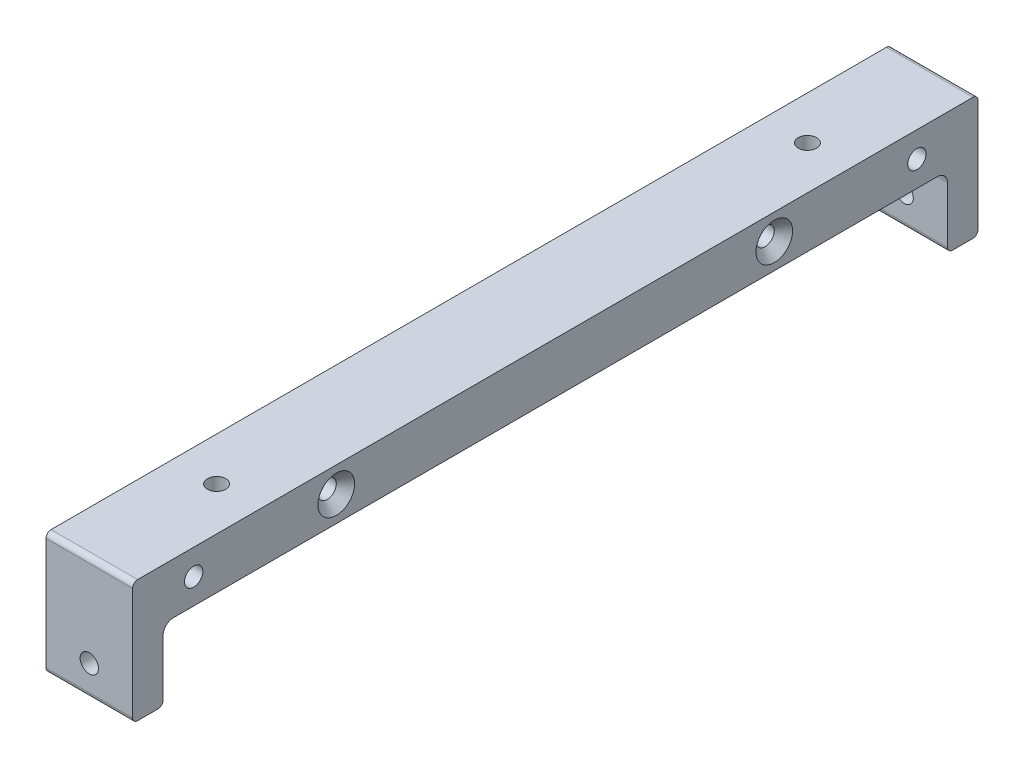
SolidWorks part; units mm, degrees
material "6061 Alloy"
ref_plane "Frontal" through (0, 0, 0) normal (0, 0, 1) x (1, 0, 0)
ref_plane "Superior" through (0, 0, 0) normal (0, 1, 0) x (1, 0, 0)
ref_plane "Direito" through (0, 0, 0) normal (1, 0, 0) x (0, 0, -1)
sketch "Sketch1" plane through (0, 0, 0) normal (0, 0, 1) x (1, 0, 0)
  line L1 (-4.25, -6) -> (4.25, -6)
  line L2 (-4.25, -6) -> (-4.25, 6)
  line L3 (-4.25, 6) -> (4.25, 6)
  line L4 (4.25, -6) -> (4.25, 6)
  line L5 (-4.25, -6) -> (4.25, 6) construction
  line L6 (-4.25, 6) -> (4.25, -6) construction
  point P0 (0, 0)
  dimension "D1" = 8.5
  dimension "D2" = 12
extrude "Boss-Extrude1" add sketch "Sketch1" along normal mid plane 83
sketch "Sketch2" plane through (4.25, 0, 0) normal (1, 0, 0) x (0, 0, -1)
  line L0 (-37.5, 1) -> (37.5, 1)
  line L1 (38.5, 0) -> (38.5, -6)
  line L2 (-41.5, -6) -> (41.5, -6) construction
  line L3 (38.5, -6) -> (-38.5, -6)
  line L4 (-38.5, -6) -> (-38.5, 0)
  line L5 (-41.5, 6) -> (41.5, 6) construction
  line L6 (-41.5, -6) -> (-41.5, 6) construction
  line L7 (41.5, -6) -> (41.5, 6) construction
  arc A0 (-37.5, 1) -> (-38.5, 0) centre (-37.5, 0) ccw
  arc A1 (37.5, 1) -> (38.5, 0) centre (37.5, 0) cw
  dimension "D4" = 1
  dimension "D5" = 1
  dimension "D1" = 5
  dimension "D2" = 3
  dimension "D3" = 3
extrude "Cut-Extrude1" cut sketch "Sketch2" against normal through all
hole_wizard "M1.6 Hole1-FixingPCB" positions "Sketch4" profile "Sketch3" countersink size "M1.6" standard "DIN" end condition through all
sketch "Sketch4" plane through (4.25, 0, 0) normal (1, 0, 0) x (0, 0, -1)
  line L0 (-41.5, 6) -> (41.5, 6) construction
  line L1 (-41.5, -6) -> (-41.5, 6) construction
  line L2 (41.5, -6) -> (41.5, 6) construction
  point P0 (-21.5, 3.5)
  point P2 (21.5, 3.5)
  dimension "D1" = 2.5
  dimension "D2" = 20
  dimension "D3" = 20
sketch "Sketch3" plane through (4.25, 3.5, 21.5) normal (0, 1, 0) x (0, 0, -1)
  line L0 (0, 0) -> (0, 8.5)
  line L1 (0, 8.5) -> (0.9, 8.5)
  line L2 (0.9, 8.5) -> (0.9, 0.9)
  line L3 (0.9, 0.9) -> (1.8, 0)
  line L5 (1.8, 0) -> (0, 0)
  line L6 (-0.9, 0.9) -> (-1.8, 0) construction
  line L11 (0, -6.35) -> (0, 107.95) construction
  dimension "Thru Hole Dia." = 1.8
  dimension "Thru Hole Depth" = 8.5
  dimension "Near C'Sink Dia." = 3.6
  dimension "Near C'Sink Angle" = 90
fillet "Fillet1" radius 0.5 6 edges at (0, 6, -41.5) (0, 6, 41.5) (0, -6, -41.5) (0, -6, -38.5) (0, -6, 38.5) (0, -6, 41.5)
hole_wizard "M1.6 Hole2-IntUnion" positions "Sketch8" profile "Sketch7" hole size "M1.6" standard "DIN"
sketch "Sketch8" plane through (0, 0, 41.5) normal (0, 0, 1) x (1, 0, 0)
  line L0 (4.25, -6) -> (-4.25, -6) construction
  point P0 (0, -3)
  dimension "D1" = 3
sketch "Sketch7" plane through (0, -3, 41.5) normal (1, 0, 0) x (0, -1, 0)
  line L0 (0, 0) -> (0, 200.5408)
  line L1 (0, 200.5408) -> (0.9, 200)
  line L2 (0.9, 200) -> (0.9, 0)
  line L5 (0.9, 0) -> (0, 0)
  line L10 (0, 200.5408) -> (-0.9, 200) construction
  line L11 (0, -6.35) -> (0, 107.95) construction
  dimension "Hole Dia." = 1.8
  dimension "Hole Depth" = 200
  dimension "Drill Angle" = 118
hole_wizard "M1.6 Hole3-ExtUnion" positions "Sketch10" profile "Sketch9" hole size "M1.6" standard "DIN"
sketch "Sketch10" plane through (4.25, 0, 0) normal (1, 0, 0) x (0, 0, -1)
  line L0 (-41, 6) -> (41, 6) construction
  line L1 (-41.5, -5.5) -> (-41.5, 5.5) construction
  line L2 (41.5, -5.5) -> (41.5, 5.5) construction
  point P0 (-35.5, 3.5)
  point P2 (35.5, 3.5)
  dimension "D1" = 2.5
  dimension "D2" = 6
  dimension "D3" = 6
sketch "Sketch9" plane through (4.25, 3.5, 35.5) normal (0, 1, 0) x (0, 0, -1)
  line L0 (0, 0) -> (0, 3.5408)
  line L1 (0, 3.5408) -> (0.9, 3)
  line L2 (0.9, 3) -> (0.9, 0)
  line L5 (0.9, 0) -> (0, 0)
  line L10 (0, 3.5408) -> (-0.9, 3) construction
  line L11 (0, -6.35) -> (0, 107.95) construction
  dimension "Hole Dia." = 1.8
  dimension "Hole Depth" = 3
  dimension "Drill Angle" = 118
hole_wizard "M1.6 Hole4-TopUnion" positions "Sketch12" profile "Sketch11" hole size "M1.6" standard "DIN"
sketch "Sketch12" plane through (-4.25, 0, 0) normal (-1, 0, 0) x (0, 0, 1)
  line L0 (41, 6) -> (-41, 6) construction
  point P0 (0, 3.5)
  dimension "D1" = 2.5
sketch "Sketch11" plane through (-4.25, 3.5, 0) normal (0, 1, 0) x (0, 0, 1)
  line L0 (0, 0) -> (0, 3.5408)
  line L1 (0, 3.5408) -> (0.9, 3)
  line L2 (0.9, 3) -> (0.9, 0)
  line L5 (0.9, 0) -> (0, 0)
  line L10 (0, 3.5408) -> (-0.9, 3) construction
  line L11 (0, -6.35) -> (0, 107.95) construction
  dimension "Hole Dia." = 1.8
  dimension "Hole Depth" = 3
  dimension "Drill Angle" = 118
hole_wizard "M1.6 Clearance Hole1" positions "Sketch15" profile "Sketch14" hole size "M1.6" standard "DIN"
sketch "Sketch15" plane through (0, 6, 0) normal (0, 1, 0) x (1, 0, 0)
  line L0 (-4.25, -41) -> (-4.25, 41) construction
  line L1 (-4.25, 41.5) -> (4.25, 41.5) construction
  line L2 (4.25, -41.5) -> (-4.25, -41.5) construction
  point P0 (0, 29)
  point P2 (0, -29)
  dimension "D1" = 4.25
  dimension "D2" = 12.5
  dimension "D3" = 12.5
sketch "Sketch14" plane through (0, 6, -29) normal (1, 0, 0) x (0, 0, 1)
  line L0 (0, 0) -> (0, 3.5408)
  line L1 (0, 3.5408) -> (0.9, 3)
  line L2 (0.9, 3) -> (0.9, 0)
  line L5 (0.9, 0) -> (0, 0)
  line L10 (0, 3.5408) -> (-0.9, 3) construction
  line L11 (0, -6.35) -> (0, 107.95) construction
  dimension "Hole Dia." = 1.8
  dimension "Hole Depth" = 3
  dimension "Drill Angle" = 118
